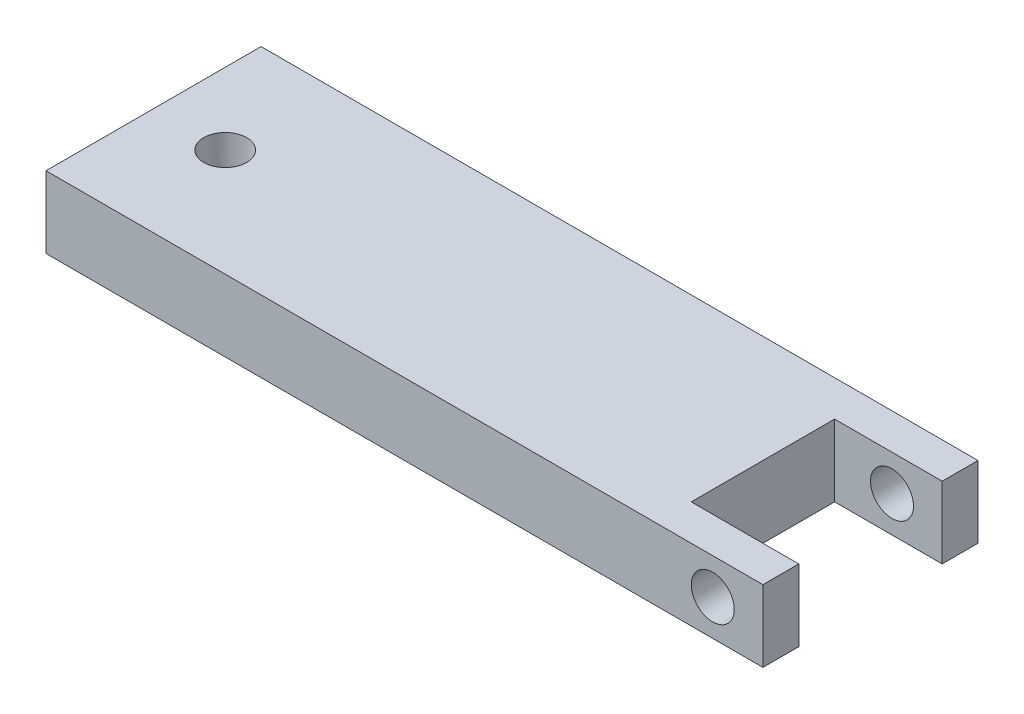
SolidWorks part; units mm, degrees
ref_plane "Front Plane" through (0, 0, 0) normal (0, 0, 1) x (1, 0, 0)
ref_plane "Top Plane" through (0, 0, 0) normal (0, 1, 0) x (1, 0, 0)
ref_plane "Right Plane" through (0, 0, 0) normal (1, 0, 0) x (0, 0, -1)
sketch "Sketch1" plane through (0, 0, 0) normal (0, 1, 0) x (1, 0, 0)
  line L1 (0, 0) -> (50, 0)
  line L2 (0, 0) -> (0, 15)
  line L3 (0, 15) -> (50, 15)
  line L4 (50, 0) -> (50, 15)
  dimension "D1" = 50
  dimension "D2" = 15
extrude "Boss-Extrude1" add sketch "Sketch1" along normal blind 5
sketch "Sketch2" plane through (0, 5, 0) normal (0, 1, 0) x (1, 0, 0)
  line L0 (0, 15) -> (0, 0) construction
  circle A0 centre (5, 7.5) radius 1.5
  point P2 (0, 0)
  point P5 (0, 7.5)
  dimension "D1" = 5
extrude "Cut-Extrude1" cut sketch "Sketch2" against normal through all and the other way through all
sketch "Sketch3" plane through (50, 0, 0) normal (1, 0, 0) x (0, 0, -1)
  line L0 (0, 5) -> (15, 5) construction
  line L1 (2.5, 5) -> (12.5, 5)
  line L2 (2.5, 5) -> (2.5, 0)
  line L3 (2.5, 0) -> (12.5, 0)
  line L4 (12.5, 5) -> (12.5, 0)
  line L5 (0, 0) -> (15, 0) construction
  point P8 (7.5, 0)
  point P9 (7.5, 0)
  dimension "D1" = 10
extrude "Cut-Extrude2" cut sketch "Sketch3" against normal blind 7.5
sketch "Sketch4" plane through (0, 0, -15) normal (0, 0, -1) x (-1, 0, 0)
  line L0 (-50, 5) -> (-50, 0) construction
  circle A0 centre (-46.5, 2.5) radius 1.5
  point P2 (0, 0)
  point P5 (-50, 2.5)
  dimension "D1" = 3.5
extrude "Cut-Extrude3" cut sketch "Sketch4" against normal through all and the other way through all
